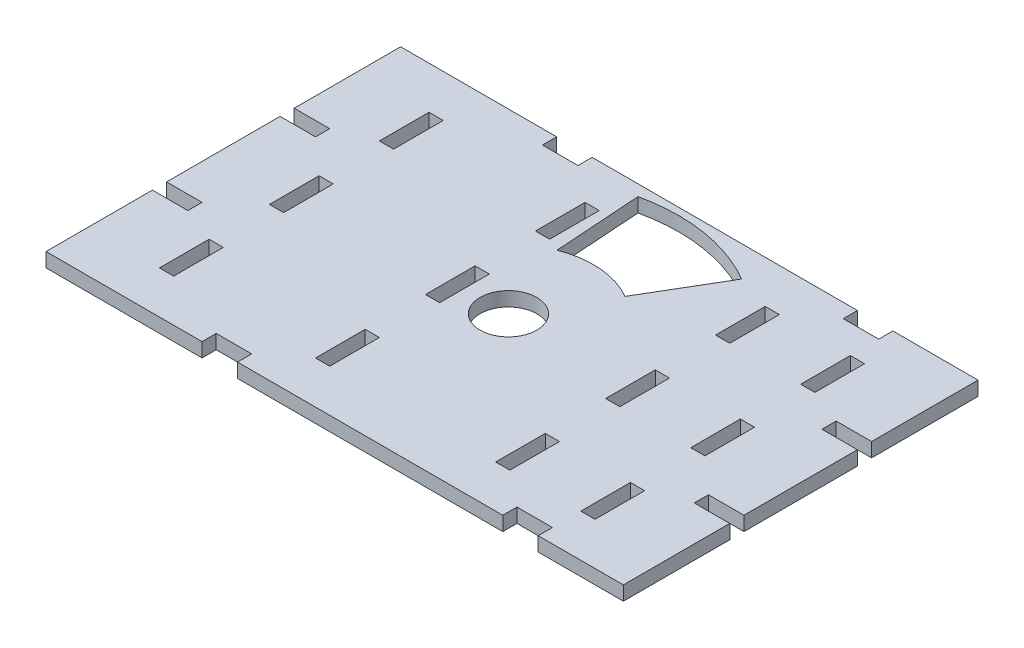
SolidWorks part; units mm, degrees
ref_plane "Front Plane" through (0, 0, 0) normal (0, 0, 1) x (1, 0, 0)
ref_plane "Top Plane" through (0, 0, 0) normal (0, 1, 0) x (1, 0, 0)
ref_plane "Right Plane" through (0, 0, 0) normal (1, 0, 0) x (0, 0, -1)
sketch "Sketch2" plane through (0, 0, 0) normal (0, 1, 0) x (1, 0, 0)
  line L1 (-50, 25) -> (50, 25)
  line L2 (-50, 25) -> (-50, -25)
  line L3 (-50, -25) -> (50, -25)
  line L4 (50, 25) -> (50, -25)
  line L5 (-50, 25) -> (50, -25) construction
  line L6 (-50, -25) -> (50, 25) construction
  circle A0 centre (0, 0) radius 4
  point P0 (0, 0)
  dimension "D3" = 8
  dimension "D1" = 100
  dimension "D2" = 50
extrude "Boss-Extrude1" add sketch "Sketch2" along normal blind 2
sketch "Sketch5" plane through (0, 0, 0) normal (0, -1, 0) x (-1, 0, 0)
  line L0 (-50, 25) -> (50, 25) construction
  line L1 (-17.2, -19) -> (-19.2, -19)
  line L2 (-17.2, -19) -> (-17.2, -12)
  line L3 (-17.2, -12) -> (-19.2, -12)
  line L4 (-19.2, -19) -> (-19.2, -12)
  line L5 (-17.2, -3.5) -> (-19.2, -3.5)
  line L6 (-17.2, -3.5) -> (-17.2, 3.5)
  line L7 (-17.2, 3.5) -> (-19.2, 3.5)
  line L8 (-19.2, -3.5) -> (-19.2, 3.5)
  line L9 (-17.2, 12) -> (-19.2, 12)
  line L10 (-17.2, 12) -> (-17.2, 19)
  line L11 (-17.2, 19) -> (-19.2, 19)
  line L12 (-19.2, 12) -> (-19.2, 19)
  line L13 (8.2, 12) -> (6.2, 12)
  line L14 (8.2, 12) -> (8.2, 19)
  line L15 (8.2, 19) -> (6.2, 19)
  line L16 (6.2, 12) -> (6.2, 19)
  line L17 (8.2, -3.5) -> (6.2, -3.5)
  line L18 (8.2, -3.5) -> (8.2, 3.5)
  line L19 (8.2, 3.5) -> (6.2, 3.5)
  line L20 (6.2, -3.5) -> (6.2, 3.5)
  line L21 (8.2, -19) -> (6.2, -19)
  line L22 (8.2, -19) -> (8.2, -12)
  line L23 (8.2, -12) -> (6.2, -12)
  line L24 (6.2, -19) -> (6.2, -12)
  line L25 (50, -25) -> (-50, -25) construction
  line L26 (-50, 25) -> (50, 25) construction
  line L27 (50, -25) -> (-50, -25) construction
  point P29 (-18.2, -19)
  dimension "D1" = 2
  dimension "D2" = 7
  dimension "D3" = 7
  dimension "D4" = 7
  dimension "D5" = 2
  dimension "D6" = 2
  dimension "D7" = 2
  dimension "D8" = 2
  dimension "D9" = 2
  dimension "D10" = 7
  dimension "D11" = 7
  dimension "D12" = 7
  dimension "D13" = 6
  dimension "D14" = 8.5
  dimension "D15" = 8.5
  dimension "D16" = 6
  dimension "D17" = 6
  dimension "D18" = 8.5
  dimension "D19" = 8.5
  dimension "D20" = 6
  dimension "D21" = 6.2
  dimension "D22" = 0
  dimension "D23" = 17.2
extrude "Cut-Extrude3" cut sketch "Sketch5" against normal blind 2
sketch "Sketch10" plane through (0, 2, 0) normal (0, 1, 0) x (1, 0, 0)
  line L0 (-5.1716, 23.4362) -> (-4.3367, 11.189)
  line L1 (12.1918, 20.6727) -> (6.0959, 10.3364)
  arc A0 (-4.3367, 11.189) -> (6.0959, 10.3364) centre (0, 0) cw
  arc A1 (-5.1716, 23.4362) -> (12.1918, 20.6727) centre (0, 0) cw
  dimension "D1" = 24
  dimension "D2" = 12
extrude "Cut-Extrude6" cut sketch "Sketch10" against normal blind 2 contours A1 L0 A0 L1
sketch "Sketch11" plane through (0, 2, 0) normal (0, 1, 0) x (1, 0, 0)
  line L0 (-50, -25) -> (50, -25) construction
  line L1 (-18.2, -25) -> (-13.2, -25)
  line L2 (-18.2, -25) -> (-18.2, -23)
  line L3 (-18.2, -23) -> (-13.2, -23)
  line L4 (-13.2, -25) -> (-13.2, -23)
  line L5 (50, 25) -> (-50, 25) construction
  line L6 (29.2, -25) -> (24.2, -25)
  line L7 (29.2, -25) -> (29.2, -23)
  line L8 (29.2, -23) -> (24.2, -23)
  line L9 (24.2, -25) -> (24.2, -23)
  line L10 (29.2, 25) -> (24.2, 25)
  line L11 (29.2, 25) -> (29.2, 23)
  line L12 (29.2, 23) -> (24.2, 23)
  line L13 (24.2, 25) -> (24.2, 23)
  line L15 (-18.2, 25) -> (-13.2, 25)
  line L16 (-18.2, 25) -> (-18.2, 23)
  line L17 (-18.2, 23) -> (-13.2, 23)
  line L18 (-13.2, 25) -> (-13.2, 23)
  dimension "D1" = 2
  dimension "D2" = 2
  dimension "D3" = 2
  dimension "D4" = 2
  dimension "D5" = 5
  dimension "D6" = 5
  dimension "D7" = 5
  dimension "D8" = 5
  dimension "D9" = 5
  dimension "D10" = 5
  dimension "D11" = 5
  dimension "D12" = 5
extrude "Cut-Extrude7" cut sketch "Sketch11" against normal blind 2
sketch "Sketch12" plane through (0, 2, 0) normal (0, 1, 0) x (1, 0, 0)
  line L0 (-50, -25) -> (-18.2, -25) construction
  line L1 (-40.2, -25) -> (-50, -25)
  line L2 (-40.2, -25) -> (-40.2, 25)
  line L3 (-40.2, 25) -> (-50, 25)
  line L4 (-50, -25) -> (-50, 25)
  line L5 (29.2, -25) -> (50, -25) construction
  line L6 (41.2, -25) -> (50, -25)
  line L7 (41.2, -25) -> (41.2, 25)
  line L8 (41.2, 25) -> (50, 25)
  line L9 (50, -25) -> (50, 25)
  line L10 (-18.2, 25) -> (-18.2, 23) construction
  point P16 (-18.2, 24)
  dimension "D1" = 22
  dimension "D2" = 12
extrude "Cut-Extrude8" cut sketch "Sketch12" against normal blind 6
sketch "Sketch13" plane through (0, 2, 0) normal (0, 1, 0) x (1, 0, 0)
  line L0 (-40.2, -25) -> (-40.2, 25) construction
  line L1 (-28.2, 19) -> (-30.2, 19)
  line L2 (-28.2, 19) -> (-28.2, 12)
  line L3 (-28.2, 12) -> (-30.2, 12)
  line L4 (-30.2, 19) -> (-30.2, 12)
  line L5 (-28.2, 3.5) -> (-30.2, 3.5)
  line L6 (-28.2, 3.5) -> (-28.2, -3.5)
  line L7 (-28.2, -3.5) -> (-30.2, -3.5)
  line L8 (-30.2, 3.5) -> (-30.2, -3.5)
  line L9 (-28.2, -12) -> (-30.2, -12)
  line L10 (-28.2, -12) -> (-28.2, -19)
  line L11 (-28.2, -19) -> (-30.2, -19)
  line L12 (-30.2, -12) -> (-30.2, -19)
  line L13 (29.2, 19) -> (31.2, 19)
  line L14 (29.2, 19) -> (29.2, 12)
  line L15 (29.2, 12) -> (31.2, 12)
  line L16 (31.2, 19) -> (31.2, 12)
  line L17 (29.2, 3.5) -> (31.2, 3.5)
  line L18 (29.2, 3.5) -> (29.2, -3.5)
  line L19 (29.2, -3.5) -> (31.2, -3.5)
  line L20 (31.2, 3.5) -> (31.2, -3.5)
  line L21 (29.2, -12) -> (31.2, -12)
  line L22 (29.2, -12) -> (29.2, -19)
  line L23 (29.2, -19) -> (31.2, -19)
  line L24 (31.2, -12) -> (31.2, -19)
  line L25 (-18.2, 25) -> (-40.2, 25) construction
  line L26 (41.2, 25) -> (41.2, -25) construction
  line L27 (41.2, 25) -> (29.2, 25) construction
  line L28 (29.2, -25) -> (41.2, -25) construction
  line L29 (-18.2, 25) -> (-40.2, 25) construction
  line L30 (-40.2, -25) -> (-18.2, -25) construction
  line L31 (-40.2, 10) -> (-35.2, 10)
  line L32 (-40.2, 10) -> (-40.2, 8)
  line L33 (-40.2, 8) -> (-35.2, 8)
  line L34 (-35.2, 10) -> (-35.2, 8)
  line L35 (-40.2, -8) -> (-35.2, -8)
  line L36 (-40.2, -8) -> (-40.2, -10)
  line L37 (-40.2, -10) -> (-35.2, -10)
  line L38 (-35.2, -8) -> (-35.2, -10)
  line L40 (41.2, 10) -> (36.2, 10)
  line L41 (41.2, 10) -> (41.2, 8)
  line L42 (41.2, 8) -> (36.2, 8)
  line L43 (36.2, 10) -> (36.2, 8)
  line L44 (41.2, -8) -> (36.2, -8)
  line L45 (41.2, -8) -> (41.2, -10)
  line L46 (41.2, -10) -> (36.2, -10)
  line L47 (36.2, -8) -> (36.2, -10)
  point P30 (30.2, 3.5)
  dimension "D1" = 2
  dimension "D2" = 2
  dimension "D3" = 2
  dimension "D4" = 2
  dimension "D5" = 2
  dimension "D6" = 2
  dimension "D7" = 10
  dimension "D8" = 10
  dimension "D9" = 10
  dimension "D10" = 7
  dimension "D11" = 7
  dimension "D12" = 7
  dimension "D13" = 7
  dimension "D14" = 7
  dimension "D15" = 7
  dimension "D16" = 10
  dimension "D17" = 10
  dimension "D18" = 10
  dimension "D19" = 6
  dimension "D20" = 8.5
  dimension "D21" = 8.5
  dimension "D22" = 6
  dimension "D23" = 6
  dimension "D24" = 8.5
  dimension "D25" = 8.5
  dimension "D26" = 6
  dimension "D27" = 2
  dimension "D28" = 2
  dimension "D29" = 15
  dimension "D30" = 5
  dimension "D31" = 5
  dimension "D32" = 15
  dimension "D33" = 16
  dimension "D34" = 2
  dimension "D35" = 2
  dimension "D36" = 5
  dimension "D37" = 5
  dimension "D38" = 0
  dimension "D39" = 0
  dimension "D40" = 15
  dimension "D41" = 16
  dimension "D42" = 15
extrude "Cut-Extrude10" cut sketch "Sketch13" against normal blind 6
